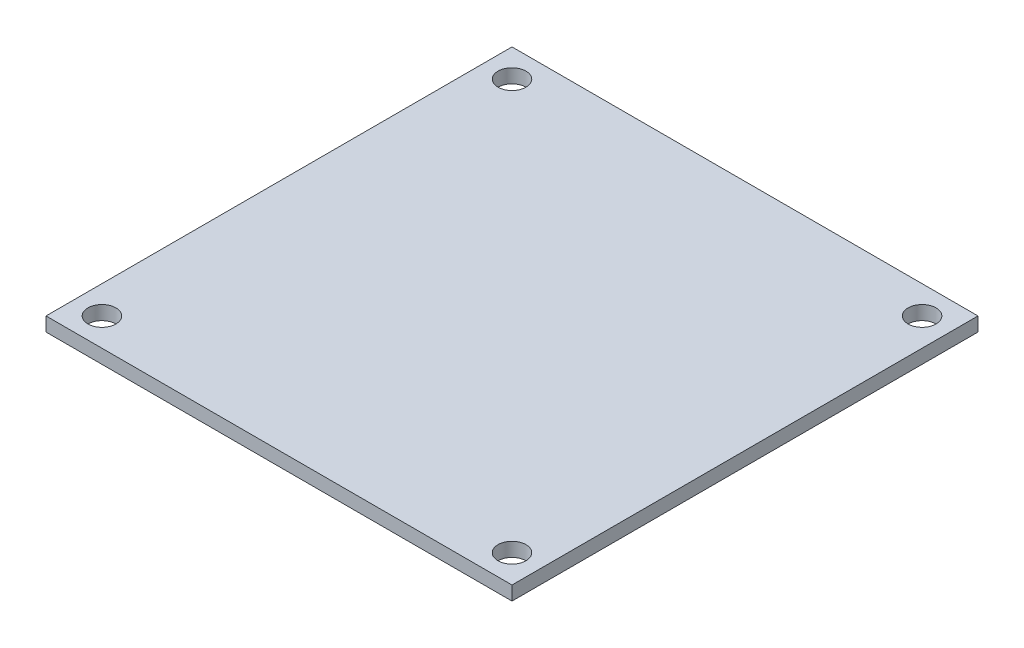
SolidWorks part; units mm, degrees
ref_plane "前视基准面" through (0, 0, 0) normal (0, 0, 1) x (1, 0, 0)
ref_plane "上视基准面" through (0, 0, 0) normal (0, 1, 0) x (1, 0, 0)
ref_plane "右视基准面" through (0, 0, 0) normal (1, 0, 0) x (0, 0, -1)
sketch "草图1" plane through (0, 0, 0) normal (0, 1, 0) x (1, 0, 0)
  line L0 (0, 0) -> (65.151, 0) construction
  line L1 (-25, -25) -> (25, -25)
  line L2 (-25, -25) -> (-25, 25)
  line L3 (-25, 25) -> (25, 25)
  line L4 (25, -25) -> (25, 25)
  line L5 (-25, -25) -> (25, 25) construction
  line L6 (-25, 25) -> (25, -25) construction
  circle A0 centre (-22, 22) radius 1.5
  circle A1 centre (22, 22) radius 1.5
  circle A4 centre (22, -22) radius 1.5
  circle A5 centre (-22, -22) radius 1.5
  point P0 (0, 0)
  dimension "D3" = 3
  dimension "D4" = 3
  dimension "D1" = 50
  dimension "D2" = 50
  dimension "D7" = 44
extrude "凸台-拉伸1" add sketch "草图1" along normal blind 1.5
